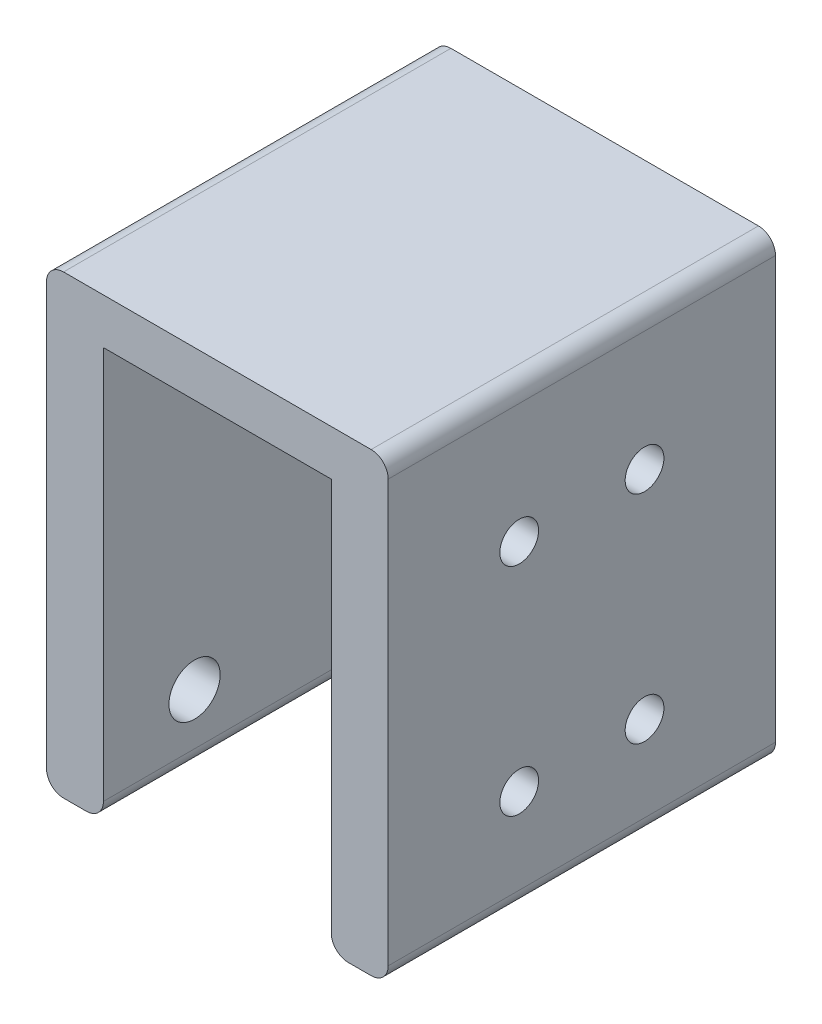
SolidWorks part; units mm, degrees
other "标注1"
sketch "草图5" plane through (0, 40, -40) normal (-0.9952, 0.0683, -0.0702) x (-0.0706, -0.003, 0.9975)
ref_plane "前视基准面" through (0, 0, 0) normal (0, 0, 1) x (1, 0, 0)
ref_plane "上视基准面" through (0, 0, 0) normal (0, 1, 0) x (1, 0, 0)
ref_plane "右视基准面" through (0, 0, 0) normal (1, 0, 0) x (0, 0, -1)
other "Configuration Table"
sketch "草图1" plane through (0, 0, 0) normal (1, 0, 0) x (0, 0, -1)
  line L1 (0, 0) -> (34, 0)
  line L2 (0, 0) -> (0, 40)
  line L3 (0, 40) -> (34, 40)
  line L4 (34, 0) -> (34, 40)
  circle A0 centre (8, 32) radius 2.25
  circle A1 centre (8, 6) radius 2.25
  circle A2 centre (26, 32) radius 2.25
  circle A3 centre (26, 6) radius 2.25
  dimension "D3" = 4.5
  dimension "D4" = 8
  dimension "D6" = 26
  dimension "D7" = 4.5
  dimension "D8" = 4.5
  dimension "D9" = 18
  dimension "D10" = 18
  dimension "D11" = 6
  dimension "D1" = 34
  dimension "D2" = 40
  dimension "D5" = 8
extrude "凸台-拉伸1" add sketch "草图1" along normal blind 5
sketch "草图2" plane through (5, 0, 0) normal (1, 0, 0) x (0, 0, -1)
  line L0 (34, 0) -> (34, 40) construction
  line L1 (0, 40) -> (34, 40)
  line L2 (0, 40) -> (0, 36)
  line L3 (0, 36) -> (34, 36)
  line L4 (34, 40) -> (34, 36)
  dimension "D1" = 4
extrude "凸台-拉伸2" add sketch "草图2" along normal blind 20
sketch "草图3" plane through (25, 0, 0) normal (1, 0, 0) x (0, 0, -1)
  line L1 (0, 40) -> (34, 40)
  line L2 (0, 40) -> (0, 0)
  line L3 (0, 0) -> (34, 0)
  line L4 (34, 40) -> (34, 0)
extrude "凸台-拉伸3" add sketch "草图3" along normal blind 5
sketch "草图4" plane through (30, 0, 0) normal (1, 0, 0) x (0, 0, -1)
  line L0 (34, 40) -> (0, 40) construction
  line L1 (0, 40) -> (0, 0) construction
  circle A0 centre (11.5, 28) radius 1.7
  circle A1 centre (22.5, 28) radius 1.7
  circle A2 centre (11.5, 9) radius 1.7
  circle A3 centre (22.5, 9) radius 1.7
  dimension "D1" = 3.4
  dimension "D2" = 3.4
  dimension "D3" = 3.4
  dimension "D4" = 3.4
  dimension "D5" = 11
  dimension "D6" = 19
  dimension "D8" = 11.5
  dimension "D9" = 31
  dimension "D10" = 11
  dimension "D7" = 12
extrude "切除-拉伸1" cut sketch "草图4" against normal blind 5
fillet "圆角1" radius 1.5 6 edges at (30, 40, -17) (0, 40, -17) (25, 0, -17) (30, 0, -17) (5, 0, -17) (0, 0, -17)
